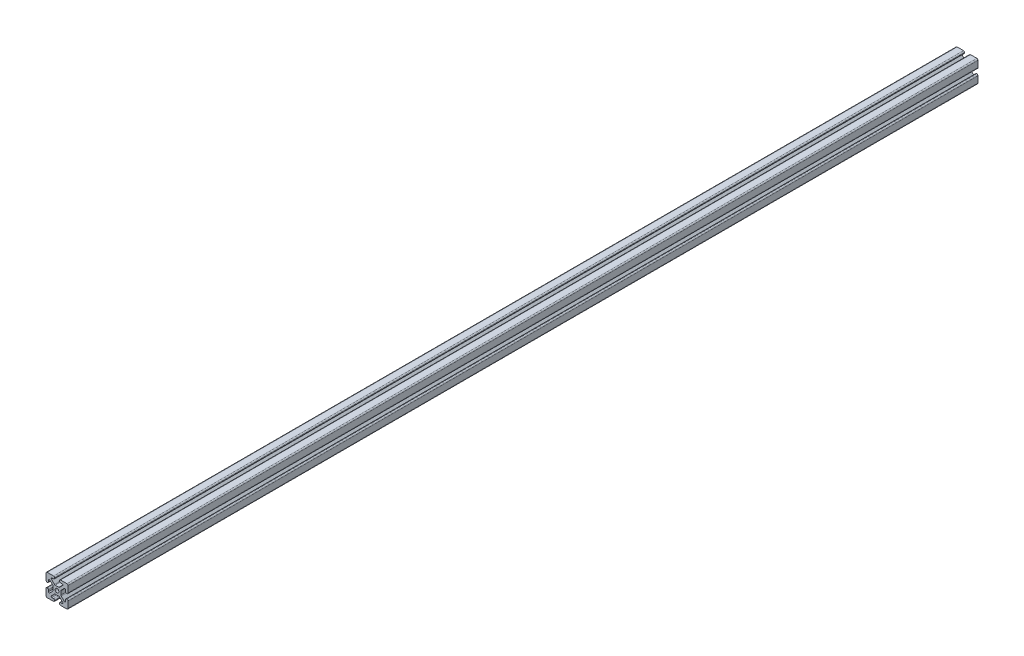
SolidWorks part; units mm, degrees
ref_plane "Front" through (0, 0, 0) normal (0, 0, 1) x (1, 0, 0)
ref_plane "Top" through (0, 0, 0) normal (0, 1, 0) x (1, 0, 0)
ref_plane "Right" through (0, 0, 0) normal (1, 0, 0) x (0, 0, -1)
sketch "Sketch1" plane through (0, 0, 0) normal (0, 0, 1) x (1, 0, 0)
  line L0 (0, 0) -> (6.7437, 0)
  line L1 (6.7437, 0) -> (6.7437, 6.7437)
  line L2 (6.7437, 6.7437) -> (-6.7437, 6.7437)
  line L3 (-6.7437, 6.7437) -> (-6.7437, -6.7437)
  line L4 (-6.7437, -6.7437) -> (6.7437, -6.7437)
  line L5 (6.7437, -6.7437) -> (6.7437, 0)
  line L6 (0, 6.7437) -> (4.064, 6.7437)
  line L7 (4.064, 6.7437) -> (4.064, 25.2303)
  line L8 (0, 6.7437) -> (-4.064, 6.7437)
  line L9 (-4.064, 6.7437) -> (-4.064, 25.2303)
  line L10 (0, 0) -> (0, 19.05)
  line L11 (0, 19.05) -> (19.05, 19.05)
  line L12 (19.05, 19.05) -> (19.05, -19.05)
  line L13 (19.05, -19.05) -> (-19.05, -19.05)
  line L14 (-19.05, -19.05) -> (-19.05, 19.05)
  line L15 (-19.05, 19.05) -> (0, 19.05)
  line L16 (4.064, 6.7437) -> (4.064, -19.05)
  line L17 (-4.064, 6.7437) -> (-4.064, -19.05)
  line L18 (6.7437, 0) -> (6.7437, -4.064)
  line L19 (6.7437, -4.064) -> (19.05, -4.064)
  line L20 (6.7437, 0) -> (6.7437, 4.064)
  line L21 (6.7437, 4.064) -> (19.05, 4.064)
  line L22 (6.7437, 4.064) -> (-19.05, 4.064)
  line L23 (6.7437, -4.064) -> (-19.05, -4.064)
  line L24 (-19.05, 19.05) -> (19.05, -19.05) construction
  line L25 (19.05, 19.05) -> (-19.05, -19.05) construction
  line L26 (-20.4868, 17.6132) -> (17.6132, -20.4868)
  line L27 (17.6132, 20.4868) -> (-20.4868, -17.6132)
  line L28 (-17.6132, 20.4868) -> (20.4868, -17.6132)
  line L29 (20.4868, 17.6132) -> (-17.6132, -20.4868)
  line L30 (-6.7437, -6.7437) -> (-6.7437, -14.7447)
  line L31 (-6.7437, -14.7447) -> (-19.05, -14.7447)
  line L32 (-6.7437, -14.7447) -> (19.05, -14.7447)
  line L33 (-6.7437, 6.7437) -> (-6.7437, 14.7447)
  line L34 (-6.7437, 14.7447) -> (19.05, 14.7447)
  line L35 (-6.7437, 14.7447) -> (-19.05, 14.7447)
  line L36 (-6.7437, 6.7437) -> (-14.7447, 6.7437)
  line L37 (-14.7447, 6.7437) -> (-14.7447, 19.05)
  line L38 (-14.7447, 6.7437) -> (-14.7447, -19.05)
  line L39 (6.7437, 6.7437) -> (14.7447, 6.7437)
  line L40 (14.7447, 6.7437) -> (14.7447, 19.05)
  line L41 (14.7447, 6.7437) -> (14.7447, -19.05)
  circle A0 centre (0, 0) radius 3.3274
  dimension "D1" = 2.032
  dimension "D2" = 2.032
extrude "Boss-Extrude1" add sketch "Sketch1" along normal blind 1574.8 contours L35 L26 L14 | L28 L37 L15 | L40 L27 L11 | L29 L34 L12 | L32 L28 L12 | L26 L41 L13 | L32 L41 L26 L13 L12 L28 | L19 L41 L28 L32 L12 | L28 L41 L32 | L41 L32 L26 | L41 L26 L32 L16 L13 | L40 L41 L21 L12 L34 L29 | L40 L29 L34 | L40 L34 L29 L12 L11 L27 | L27 L40 L11 L7 L34 | L34 L40 L27 | L37 L28 L35 L34 L9 L15 | L37 L35 L28 | L35 L37 L28 L15 L14 L26 | L26 L37 L35 | L38 L37 L26 L35 L14 L22 | L38 L23 L14 L31 L27 | L38 L27 L31 | L27 L31 L14 | L38 L31 L27 L14 L13 L29 | L38 L29 L13 | L31 L38 L29 | L29 L38 L13 L17 L32 L31 | L27 L38 L31 L29 L30 L3 L23 | L4 L30 L29 L17 | L17 L23 L3 L4 | L41 L28 L19 L5 L4 L16 L26 L32 | L29 L40 L34 L27 L7 L2 L39 | L39 L1 L21 L29 | L37 L26 L36 L33 L28 L35 | L33 L2 L9 L28 | L3 L36 L26 L22 | L22 L17 L2 L3 | L3 L26 L17 L22 | L27 L17 L26 L3 | A0 L28 L22 L17 L26 | L28 L8 L17 L22 | L2 L28 L22 L10 | A0 L10 L22 L28 | A0 L27 L22 L10 | L27 L6 L10 L22 | L2 L27 L22 L16 | L22 L1 L2 L16 | L29 L20 L22 L16 | L1 L29 L16 L0 | A0 L29 L16 L22 L27 | A0 L0 L16 L29 | A0 L28 L16 L0 | L16 L28 L18 L0 | L28 L16 L23 L5 | A0 L26 L23 L16 L28 | L5 L23 L16 L4 | L23 L26 L4 L16 | L23 L29 L4 L26 | A0 L29 L23 L26 | A0 L27 L17 L23 L29 | L17 L27 L3 L23 | A0 L26 L17 L27 | L4 L26 L16 | L28 L5 L19 | L29 L21 L20 | L7 L27 L2 | L28 L9 L8 | L22 L26 L3 | L3 L27 L23 | L29 L4 L17 | L29 L23 L17 L4
fillet "Fillet2" radius 2.032 8 edges at (-6.7437, -3.87, 787.4) (-6.7437, 3.87, 787.4) (-3.87, 6.7437, 787.4) (3.87, 6.7437, 787.4) (6.7437, 3.87, 787.4) (6.7437, -3.87, 787.4) (-3.87, -6.7437, 787.4) (3.87, -6.7437, 787.4)
fillet "Fillet3" radius 2.032 20 edges at (14.7447, 4.064, 787.4) (14.7447, -4.064, 787.4) (19.05, -4.064, 787.4) (19.05, -19.05, 787.4) (4.064, -19.05, 787.4) (4.064, -14.7447, 787.4) (-4.064, -14.7447, 787.4) (-4.064, -19.05, 787.4) (-19.05, -19.05, 787.4) (-19.05, -4.064, 787.4) (-14.7447, -4.064, 787.4) (-14.7447, 4.064, 787.4) (-19.05, 4.064, 787.4) (-19.05, 19.05, 787.4) (-4.064, 19.05, 787.4) (-4.064, 14.7447, 787.4) (4.064, 14.7447, 787.4) (4.064, 19.05, 787.4) (19.05, 19.05, 787.4) (19.05, 4.064, 787.4)
fillet "Fillet4" radius 1.27 8 edges at (14.7447, 11.871, 787.4) (14.7447, -11.871, 787.4) (11.871, -14.7447, 787.4) (-11.871, -14.7447, 787.4) (-14.7447, -11.871, 787.4) (-14.7447, 11.871, 787.4) (-11.871, 14.7447, 787.4) (11.871, 14.7447, 787.4)
